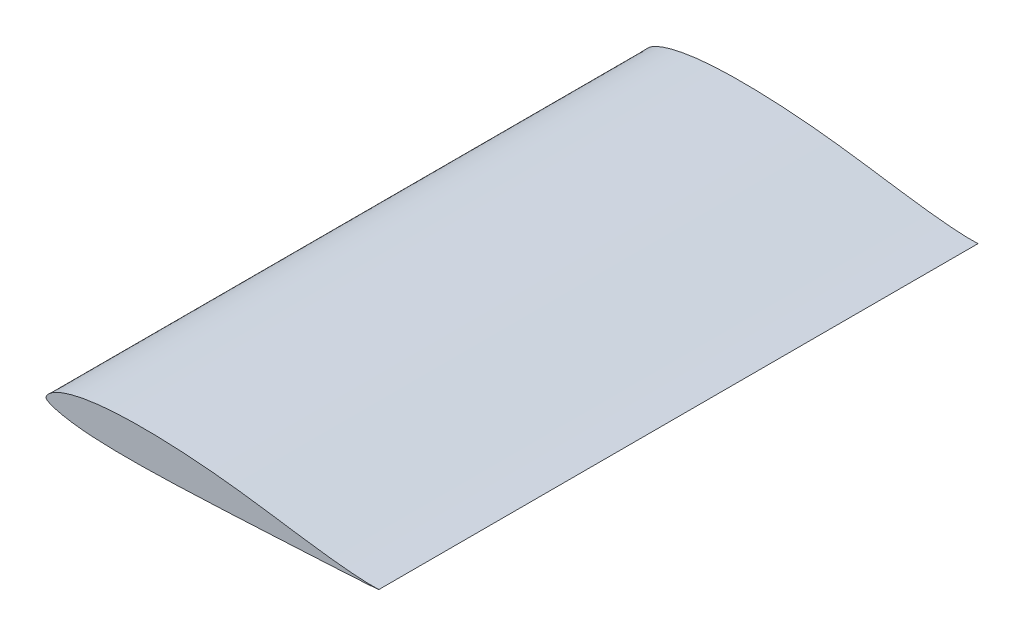
SolidWorks part; units mm, degrees
ref_plane "Front Plane" through (0, 0, 0) normal (0, 0, 1) x (1, 0, 0)
ref_plane "Top Plane" through (0, 0, 0) normal (0, 1, 0) x (1, 0, 0)
ref_plane "Right Plane" through (0, 0, 0) normal (1, 0, 0) x (0, 0, -1)
sketch "Sketch1" plane through (0, 0, 0) normal (0, 0, 1) x (1, 0, 0)
  spline S0 degree 3 poles (100, 0) (99.8731, -0.0071) (99.5859, -0.022) (99.0723, -0.0417) (98.395, -0.054) (97.5264, -0.0484) (96.4743, -0.0203) (95.2466, 0.0314) (93.8506, 0.1096) (92.2934, 0.2165) (90.584, 0.3553) (88.7334, 0.531) (86.7545, 0.7439) (84.6593, 0.9899) (82.4593, 1.2664) (80.1654, 1.5708) (77.789, 1.8995) (75.3412, 2.249) (72.8329, 2.6139) (70.2739, 2.988) (67.6746, 3.3671) (65.0453, 3.747) (62.3931, 4.117) (59.7222, 4.4661) (57.0391, 4.7981) (54.3511, 5.1121) (51.6638, 5.3986) (48.9816, 5.6526) (46.3101, 5.8796) (43.6566, 6.0801) (41.0282, 6.2495) (38.4317, 6.3872) (35.8744, 6.4957) (33.3639, 6.5737) (30.907, 6.618) (28.5104, 6.6289) (26.181, 6.6084) (23.9252, 6.5538) (21.7477, 6.4597) (19.6526, 6.3304) (17.6448, 6.1696) (15.7296, 5.9748) (13.9109, 5.7433) (12.1916, 5.481) (10.5754, 5.1916) (9.0667, 4.8734) (7.6685, 4.527) (6.3827, 4.1587) (5.2117, 3.7714) (4.1584, 3.3617) (3.2229, 2.9331) (2.4031, 2.4958) (1.7001, 2.0549) (1.1171, 1.6113) (0.6544, 1.1744) (0.3054, 0.7558) (0.0876, 0.3713) (-0.0375, 0.0106) (0.0834, -0.3474) (0.4219, -0.6082) (0.8742, -0.8882) (1.4854, -1.1653) (2.2368, -1.4419) (3.1307, -1.7088) (4.1616, -1.9668) (5.3267, -2.2128) (6.6225, -2.4429) (8.0456, -2.6547) (9.5917, -2.848) (11.257, -3.02) (13.0387, -3.1652) (14.9339, -3.2844) (16.9379, -3.3811) (19.046, -3.4536) (21.2535, -3.4982) (23.556, -3.5188) (25.9473, -3.5195) (28.4201, -3.4998) (30.9674, -3.4595) (33.5819, -3.4019) (36.2555, -3.3294) (38.9797, -3.242) (41.7464, -3.1405) (44.5471, -3.028) (47.3728, -2.9068) (50.2138, -2.778) (53.0606, -2.6434) (55.9036, -2.5046) (58.7329, -2.3631) (61.5385, -2.2205) (65.2036, -2.0318) (67.9323, -1.8888) (69.7359, -1.7939) knots 0 0 0 0 0.002209 0.005 0.008935 0.013986 0.0201 0.027233 0.035349 0.044409 0.054368 0.065167 0.076726 0.088972 0.101844 0.115276 0.129202 0.143554 0.158263 0.173271 0.188517 0.203934 0.219458 0.235074 0.250763 0.266462 0.282126 0.297747 0.313303 0.328739 0.344012 0.359094 0.373944 0.388512 0.402762 0.416665 0.430179 0.44326 0.455893 0.46807 0.479753 0.49091 0.501536 0.511624 0.521145 0.530078 0.538426 0.546183 0.553327 0.559863 0.565821 0.571207 0.576006 0.580234 0.583919 0.58706 0.589647 0.591628 0.59346 0.595772 0.598876 0.602753 0.607392 0.612796 0.618961 0.625865 0.633495 0.641838 0.650877 0.660582 0.670942 0.681955 0.693595 0.705824 0.718625 0.731983 0.745856 0.760199 0.774976 0.790149 0.805665 0.821475 0.837536 0.853799 0.870208 0.886708 0.903243 0.919758 0.936194 0.952494 0.968599 1 1 1 1
  spline S1 degree 3 poles (55.908, -2.5038) (57.7887, -2.4109) (60.5943, -2.2691) (64.3105, -2.0778) (67.0393, -1.9356) (69.7151, -1.795) (72.3286, -1.6572) (74.8704, -1.5224) (77.3316, -1.3911) (79.7037, -1.2638) (81.9782, -1.1412) (84.1472, -1.0235) (86.203, -0.9111) (88.1383, -0.8045) (89.9458, -0.7043) (91.6189, -0.6099) (93.1515, -0.5213) (94.5382, -0.4386) (95.7737, -0.3616) (96.8535, -0.2898) (97.7744, -0.2227) (98.5355, -0.1573) (99.1368, -0.0941) (99.6071, -0.0399) (99.8773, -0.011) (100, 0) knots 0 0 0 0 0.1279 0.190821 0.25276 0.313503 0.372831 0.430531 0.486402 0.540251 0.591887 0.641127 0.6878 0.731739 0.772779 0.810765 0.845568 0.87706 0.905123 0.929654 0.950569 0.967842 0.981542 0.991633 1 1 1 1
  point P0 (100, 0)
  point P1 (99.9053, -0.0052)
  point P3 (99.6193, -0.0195)
  point P4 (99.138, -0.0378)
  point P5 (98.4591, -0.0504)
  point P6 (97.5876, -0.0462)
  point P7 (96.533, -0.0194)
  point P8 (95.3032, 0.0317)
  point P9 (93.9049, 0.1093)
  point P10 (92.3453, 0.216)
  point P11 (90.6324, 0.3551)
  point P12 (88.7773, 0.5306)
  point P13 (86.7941, 0.7428)
  point P14 (84.6953, 0.9885)
  point P15 (82.4916, 1.2649)
  point P16 (80.1939, 1.5691)
  point P17 (77.8135, 1.8978)
  point P18 (75.3617, 2.2471)
  point P19 (72.8499, 2.6117)
  point P20 (70.2875, 2.9859)
  point P21 (67.6842, 3.3651)
  point P22 (65.0511, 3.744)
  point P23 (62.3978, 4.1125)
  point P24 (59.726, 4.4625)
  point P25 (57.0393, 4.795)
  point P26 (54.3486, 5.1078)
  point P27 (51.6609, 5.3936)
  point P28 (48.9774, 5.6487)
  point P29 (46.3028, 5.876)
  point P30 (43.6469, 6.0759)
  point P31 (41.017, 6.2452)
  point P32 (38.4182, 6.3833)
  point P33 (35.858, 6.4915)
  point P34 (33.3455, 6.5687)
  point P35 (30.887, 6.6127)
  point P36 (28.488, 6.6235)
  point P37 (26.1562, 6.6021)
  point P38 (23.8998, 6.546)
  point P39 (21.7219, 6.4518)
  point P40 (19.6247, 6.3222)
  point P41 (17.6152, 6.1599)
  point P42 (15.7002, 5.9635)
  point P43 (13.8813, 5.7317)
  point P44 (12.1605, 5.4685)
  point P45 (10.5438, 5.1771)
  point P46 (7.6379, 4.5102)
  point P47 (6.3515, 4.14)
  point P48 (9.0359, 4.8574)
  point P49 (5.1822, 3.75)
  point P50 (4.1319, 3.339)
  point P51 (3.1978, 2.9096)
  point P52 (2.379, 2.4699)
  point P53 (1.6797, 2.0265)
  point P54 (1.1013, 1.5819)
  point P55 (0.6412, 1.1431)
  point P56 (0.3001, 0.7219)
  point P57 (0.0832, 0.3316)
  point P58 (0.0001, -0.0112)
  point P59 (0.0957, -0.3011)
  point P60 (0.3869, -0.574)
  point P61 (0.842, -0.8563)
  point P62 (1.4477, -1.1401)
  point P63 (2.198, -1.4194)
  point P64 (3.0904, -1.69)
  point P65 (4.1217, -1.9504)
  point P66 (5.2871, -2.1982)
  point P67 (6.583, -2.4299)
  point P68 (8.0068, -2.6435)
  point P69 (9.5543, -2.8379)
  point P70 (11.22, -3.0103)
  point P71 (13.0017, -3.1568)
  point P72 (14.8981, -3.2776)
  point P73 (16.9043, -3.375)
  point P74 (19.0132, -3.4476)
  point P75 (21.2216, -3.4935)
  point P76 (23.5264, -3.5153)
  point P77 (25.9203, -3.5162)
  point P78 (28.3951, -3.4968)
  point P79 (30.9446, -3.4573)
  point P80 (33.5621, -3.4002)
  point P81 (36.2385, -3.3277)
  point P82 (38.9652, -3.2404)
  point P83 (41.7347, -3.1393)
  point P84 (44.5387, -3.027)
  point P85 (47.3676, -2.9058)
  point P86 (50.2118, -2.7772)
  point P87 (53.0618, -2.6426)
  point P88 (55.908, -2.5038)
  point P89 (58.7407, -2.3624)
  point P90 (61.5497, -2.2196)
  point P91 (64.325, -2.0768)
  point P92 (67.0568, -1.9345)
  point P93 (69.7359, -1.7939)
  point P94 (72.3525, -1.6558)
  point P95 (74.8973, -1.5208)
  point P96 (77.3613, -1.3894)
  point P97 (79.7362, -1.262)
  point P98 (82.0134, -1.1391)
  point P99 (84.1849, -1.0213)
  point P100 (86.2432, -0.9087)
  point P101 (88.1809, -0.8021)
  point P102 (89.9906, -0.7015)
  point P103 (89.9906, -0.7015)
  point P104 (93.2001, -0.518)
  point P105 (88.1809, -0.8021)
  point P106 (91.6657, -0.6069)
  point P107 (94.5885, -0.435)
  point P108 (95.8255, -0.3575)
  point P109 (96.9066, -0.285)
  point P110 (97.8277, -0.2166)
  point P111 (98.5877, -0.1501)
  point P112 (99.1895, -0.0874)
  point P113 (99.6324, -0.0377)
  point P114 (99.6324, -0.0377)
  point P115 (99.9067, -0.0088)
  point P122 (0, 0)
extrude "Boss-Extrude4" add sketch "Sketch1" along normal blind 180 contours S0 S1
